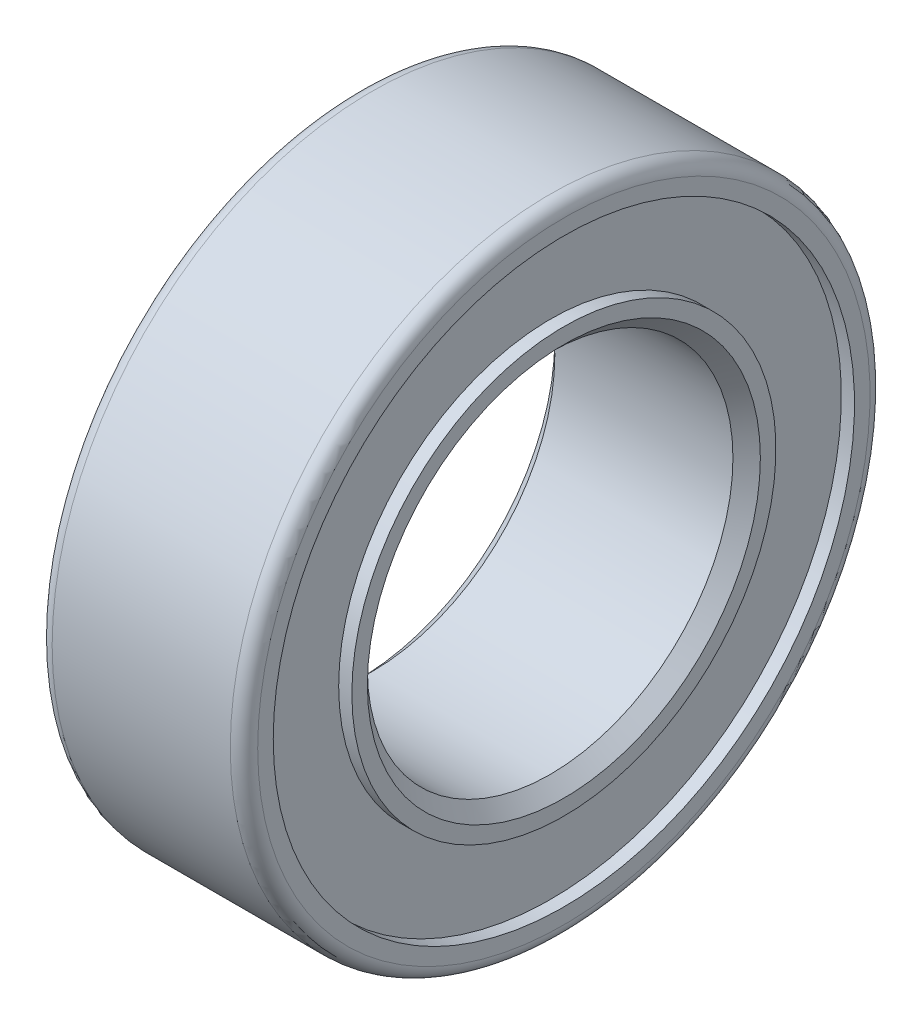
SolidWorks part; units mm, degrees
material "Plain Carbon Steel"
ref_plane "Front Plane" through (0, 0, 0) normal (0, 0, 1) x (1, 0, 0)
ref_plane "Top Plane" through (0, 0, 0) normal (0, 1, 0) x (1, 0, 0)
ref_plane "Right Plane" through (0, 0, 0) normal (1, 0, 0) x (0, 0, -1)
ref_plane "Plane1" through (0, 0, 0) normal (0, 0, -1) x (-1, 0, 0)
sketch "Sketch1" plane through (0, 0, 0) normal (0, 0, -1) x (-1, 0, 0)
  line L0 (-3.5702, 6.8263) -> (-3.094, 6.35)
  line L1 (-3.094, 6.35) -> (3.094, 6.35)
  line L2 (3.094, 6.35) -> (3.5702, 6.8262)
  line L3 (3.5702, 6.8262) -> (3.5702, 7.366)
  line L4 (3.5702, 7.366) -> (3.113, 7.366)
  line L5 (3.113, 7.366) -> (3.113, 10.0965)
  line L6 (3.113, 10.0965) -> (3.5702, 10.0965)
  line L7 (3.5702, 10.0965) -> (3.5702, 10.6363)
  line L8 (3.094, 11.1125) -> (-3.094, 11.1125)
  line L9 (-3.5702, 10.6363) -> (-3.5702, 10.0965)
  line L10 (-3.5702, 10.0965) -> (-3.113, 10.0965)
  line L11 (-3.113, 10.0965) -> (-3.113, 7.366)
  line L12 (-3.113, 7.366) -> (-3.5702, 7.366)
  line L13 (-3.5702, 7.366) -> (-3.5702, 6.8263)
  line L14 (-3.5715, 0) -> (3.5715, 0) construction
  arc A0 (3.5702, 10.6363) -> (3.094, 11.1125) centre (3.094, 10.6363) ccw
  arc A1 (-3.094, 11.1125) -> (-3.5702, 10.6363) centre (-3.094, 10.6363) ccw
revolve "Revolve1" add sketch "Sketch1" angle 360 about L14
